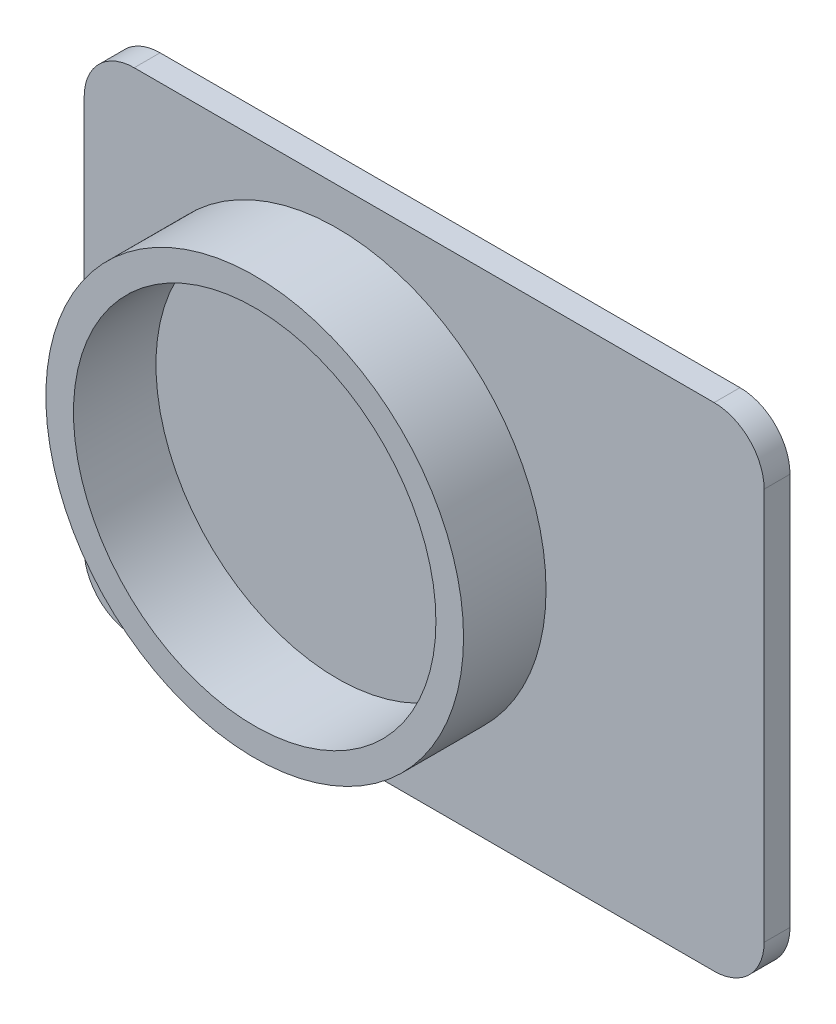
SolidWorks part; units mm, degrees
ref_plane "Front Plane" through (0, 0, 0) normal (0, 0, 1) x (1, 0, 0)
ref_plane "Top Plane" through (0, 0, 0) normal (0, 1, 0) x (1, 0, 0)
ref_plane "Right Plane" through (0, 0, 0) normal (1, 0, 0) x (0, 0, -1)
sketch "Sketch1" plane through (0, 0, 0) normal (0, 0, 1) x (1, 0, 0)
  line L1 (23.2, -19.7) -> (-23.2, -19.7)
  line L2 (27.2, -15.7) -> (27.2, 15.7)
  line L3 (23.2, 19.7) -> (-23.2, 19.7)
  line L4 (-27.2, -15.7) -> (-27.2, 15.7)
  line L5 (27.2, -19.7) -> (-27.2, 19.7) construction
  line L6 (27.2, 19.7) -> (-27.2, -19.7) construction
  arc A0 (-23.2, 19.7) -> (-27.2, 15.7) centre (-23.2, 15.7) ccw
  arc A1 (27.2, 15.7) -> (23.2, 19.7) centre (23.2, 15.7) ccw
  arc A2 (23.2, -19.7) -> (27.2, -15.7) centre (23.2, -15.7) ccw
  arc A3 (-27.2, -15.7) -> (-23.2, -19.7) centre (-23.2, -15.7) ccw
  point P0 (0, 0)
  dimension "D3" = 4
  dimension "D4" = 4
  dimension "D5" = 4
  dimension "D6" = 4
  dimension "D1" = 39.4
  dimension "D2" = 54.4
extrude "Boss-Extrude1" add sketch "Sketch1" along normal blind 2.07
sketch "Sketch3" plane through (0, 0, 0) normal (0, 0, 1) x (1, 0, 0)
  circle A0 centre (-6.9588, 0) radius 14.5
extrude "Extrude-Thin1" add sketch "Sketch3" along normal blind 8.67 thin
sketch "Sketch4" plane through (0, 0, 0) normal (0, 0, 1) x (1, 0, 0)
  line L0 (0, 19.7) -> (0, -19.7) construction
  line L1 (23.2, 19.7) -> (-23.2, 19.7) construction
  line L2 (-23.2, -19.7) -> (23.2, -19.7) construction
